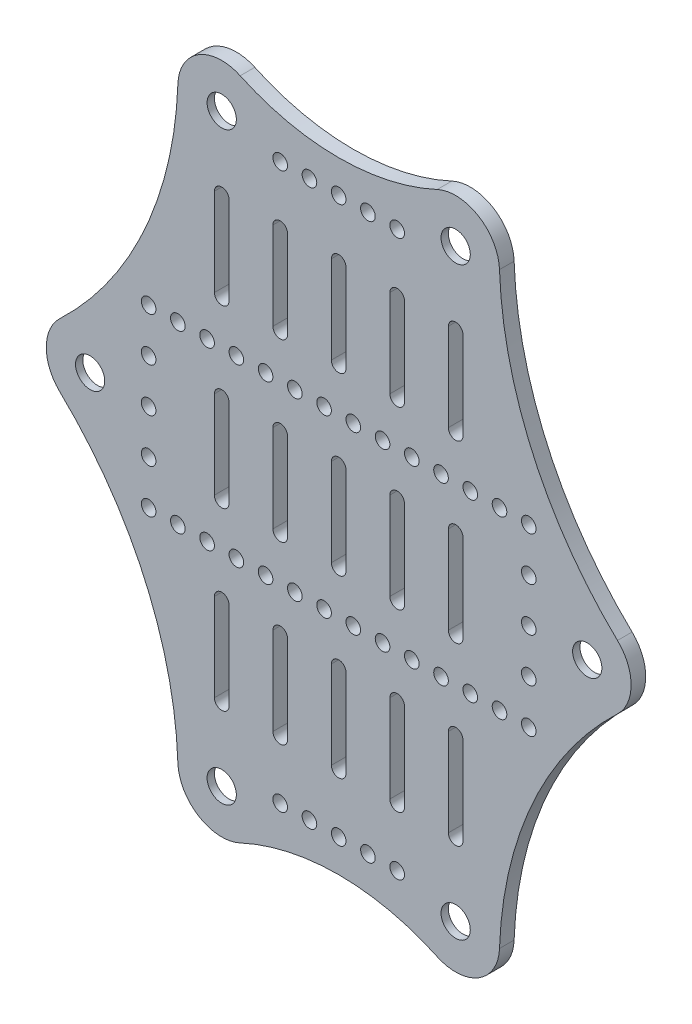
SolidWorks part; units mm, degrees
ref_plane "前视基准面" through (0, 0, 0) normal (0, 0, 1) x (1, 0, 0)
ref_plane "上视基准面" through (0, 0, 0) normal (0, 1, 0) x (1, 0, 0)
ref_plane "右视基准面" through (0, 0, 0) normal (1, 0, 0) x (0, 0, -1)
other "Configuration Table"
sketch "Sketch1" plane through (0, 0, 0) normal (0, 0, 1) x (1, 0, 0)
  line L0 (0, 0) -> (0, 100) construction
  line L1 (0, 100) -> (40, 100) construction
  line L2 (0, 0) -> (85, 0) construction
  circle A1 centre (85, 0) radius 15
  circle A2 centre (40, 100) radius 15
  circle A3 centre (-85, 0) radius 15
  circle A4 centre (-40, 100) radius 15
  circle A5 centre (40, -100) radius 15
  circle A6 centre (-40, -100) radius 15
  arc A7 (-33.6842, 113.6055) -> (33.6842, 113.6055) centre (0, 186.1684) ccw
  arc A8 (-33.6842, -113.6055) -> (33.6842, -113.6055) centre (0, -186.1684) cw
  arc A9 (-95.3356, 10.8708) -> (-54.9908, 100.526) centre (-184.9108, 105.0849) ccw
  arc A10 (95.3356, 10.8708) -> (54.9908, 100.526) centre (184.9108, 105.0849) cw
  arc A11 (95.3356, -10.8708) -> (54.9908, -100.526) centre (184.9108, -105.0849) ccw
  arc A12 (-95.3356, -10.8708) -> (-54.9908, -100.526) centre (-184.9108, -105.0849) cw
  dimension "D1" = 30
  dimension "D2" = 30
  dimension "D6" = 80
  dimension "D7" = 130
  dimension "D3" = 40
  dimension "D4" = 85
  dimension "D5" = 100
extrude "Boss-Extrude1" add sketch "Sketch1" along normal blind 5 contours A3 A12 A6 A8 A5 A11 A1 A10 A2 A7 A4 A9 | A3 | A4 | A2 | A1 | A5 | A6 A7
sketch "Sketch2" plane through (0, 0, 0) normal (0, 0, -1) x (-1, 0, 0)
  line L0 (0, 0) -> (0, 91.5521) construction
  line L1 (0, 0) -> (39.9574, 0) construction
  circle A0 centre (-40, 100) radius 5
  circle A1 centre (-85, 0) radius 5
  circle A2 centre (85, 0) radius 5
  circle A3 centre (40, 100) radius 5
  circle A4 centre (40, -100) radius 5
  circle A5 centre (-40, -100) radius 5
  dimension "D1" = 10
extrude "Cut-Extrude1" cut sketch "Sketch2" against normal through all
sketch "Sketch5" plane through (0, 0, 0) normal (0, 0, -1) x (-1, 0, 0)
  line L0 (0, 95) -> (0, 106.1684) construction
  line L1 (0, 95) -> (20, 95) construction
  line L2 (0, -95) -> (0, -106.1684) construction
  line L3 (0, 0) -> (50.0339, 0) construction
  line L5 (0, -95) -> (20, -95) construction
  circle A0 centre (20, 95) radius 2.5
  circle A1 centre (0, 95) radius 2.5
  circle A2 centre (10, 95) radius 2.5
  circle A17 centre (10, -95) radius 2.5
  circle A18 centre (0, -95) radius 2.5
  circle A19 centre (20, -95) radius 2.5
  arc A20 (-33.6842, 113.6055) -> (33.6842, 113.6055) centre (0, 186.1684) ccw construction
  circle A21 centre (-20, 95) radius 2.5
  circle A22 centre (-10, 95) radius 2.5
  arc A23 (33.6842, -113.6055) -> (-33.6842, -113.6055) centre (0, -186.1684) ccw construction
  circle A24 centre (-20, -95) radius 2.5
  circle A25 centre (-10, -95) radius 2.5
  dimension "D1" = 5
  dimension "D2" = 5
  dimension "D4" = 5
  dimension "D3" = 95
  dimension "D5" = 10
extrude "Cut-Extrude4" cut sketch "Sketch5" against normal blind 12.5
sketch "Sketch6" plane through (0, 0, 5) normal (0, 0, 1) x (1, 0, 0)
  line L110 (0, 0) -> (0, 75) construction
  line L111 (0, 75) -> (40, 75) construction
  line L112 (40, 75) -> (40, 45) construction
  line L113 (42.5, 75) -> (42.5, 45)
  line L114 (37.5, 75) -> (37.5, 45)
  line L115 (20, 75) -> (20, 45) construction
  line L116 (22.5, 75) -> (22.5, 45)
  line L117 (17.5, 75) -> (17.5, 45)
  line L118 (0, 75) -> (0, 45) construction
  line L119 (2.5, 75) -> (2.5, 45)
  line L120 (-2.5, 75) -> (-2.5, 45)
  line L121 (-20, 75) -> (-20, 45) construction
  line L122 (-17.5, 75) -> (-17.5, 45)
  line L123 (-22.5, 75) -> (-22.5, 45)
  line L124 (-40, 75) -> (-40, 45) construction
  line L125 (-37.5, 75) -> (-37.5, 45)
  line L126 (-42.5, 75) -> (-42.5, 45)
  line L127 (40, 100) -> (0, 100) construction
  line L128 (0, 15) -> (40, 15) construction
  line L129 (40, 15) -> (40, -15) construction
  line L130 (42.5, 15) -> (42.5, -15)
  line L131 (37.5, 15) -> (37.5, -15)
  line L132 (20, 15) -> (20, -15) construction
  line L133 (22.5, 15) -> (22.5, -15)
  line L134 (17.5, 15) -> (17.5, -15)
  line L135 (0, 15) -> (0, -15) construction
  line L136 (2.5, 15) -> (2.5, -15)
  line L137 (-2.5, 15) -> (-2.5, -15)
  line L138 (-20, 15) -> (-20, -15) construction
  line L139 (-17.5, 15) -> (-17.5, -15)
  line L140 (-22.5, 15) -> (-22.5, -15)
  line L141 (-40, 15) -> (-40, -15) construction
  line L142 (-37.5, 15) -> (-37.5, -15)
  line L143 (-42.5, 15) -> (-42.5, -15)
  line L144 (0, -45) -> (40, -45) construction
  line L145 (40, -45) -> (40, -75) construction
  line L146 (42.5, -45) -> (42.5, -75)
  line L147 (37.5, -45) -> (37.5, -75)
  line L148 (20, -45) -> (20, -75) construction
  line L149 (22.5, -45) -> (22.5, -75)
  line L150 (17.5, -45) -> (17.5, -75)
  line L151 (0, -45) -> (0, -75) construction
  line L152 (2.5, -45) -> (2.5, -75)
  line L153 (-2.5, -45) -> (-2.5, -75)
  line L154 (-20, -45) -> (-20, -75) construction
  line L155 (-17.5, -45) -> (-17.5, -75)
  line L156 (-22.5, -45) -> (-22.5, -75)
  line L157 (-40, -45) -> (-40, -75) construction
  line L158 (-37.5, -45) -> (-37.5, -75)
  line L159 (-42.5, -45) -> (-42.5, -75)
  arc A90 (42.5, 75) -> (37.5, 75) centre (40, 75) ccw
  arc A91 (37.5, 45) -> (42.5, 45) centre (40, 45) ccw
  arc A92 (22.5, 75) -> (17.5, 75) centre (20, 75) ccw
  arc A93 (17.5, 45) -> (22.5, 45) centre (20, 45) ccw
  arc A94 (2.5, 75) -> (-2.5, 75) centre (0, 75) ccw
  arc A95 (-2.5, 45) -> (2.5, 45) centre (0, 45) ccw
  arc A96 (-17.5, 75) -> (-22.5, 75) centre (-20, 75) ccw
  arc A97 (-22.5, 45) -> (-17.5, 45) centre (-20, 45) ccw
  arc A98 (-37.5, 75) -> (-42.5, 75) centre (-40, 75) ccw
  arc A99 (-42.5, 45) -> (-37.5, 45) centre (-40, 45) ccw
  arc A100 (42.5, 15) -> (37.5, 15) centre (40, 15) ccw
  arc A101 (37.5, -15) -> (42.5, -15) centre (40, -15) ccw
  arc A102 (22.5, 15) -> (17.5, 15) centre (20, 15) ccw
  arc A103 (17.5, -15) -> (22.5, -15) centre (20, -15) ccw
  arc A104 (2.5, 15) -> (-2.5, 15) centre (0, 15) ccw
  arc A105 (-2.5, -15) -> (2.5, -15) centre (0, -15) ccw
  arc A106 (-17.5, 15) -> (-22.5, 15) centre (-20, 15) ccw
  arc A107 (-22.5, -15) -> (-17.5, -15) centre (-20, -15) ccw
  arc A108 (-37.5, 15) -> (-42.5, 15) centre (-40, 15) ccw
  arc A109 (-42.5, -15) -> (-37.5, -15) centre (-40, -15) ccw
  arc A110 (42.5, -45) -> (37.5, -45) centre (40, -45) ccw
  arc A111 (37.5, -75) -> (42.5, -75) centre (40, -75) ccw
  arc A112 (22.5, -45) -> (17.5, -45) centre (20, -45) ccw
  arc A113 (17.5, -75) -> (22.5, -75) centre (20, -75) ccw
  arc A114 (2.5, -45) -> (-2.5, -45) centre (0, -45) ccw
  arc A115 (-2.5, -75) -> (2.5, -75) centre (0, -75) ccw
  arc A116 (-17.5, -45) -> (-22.5, -45) centre (-20, -45) ccw
  arc A117 (-22.5, -75) -> (-17.5, -75) centre (-20, -75) ccw
  arc A118 (-37.5, -45) -> (-42.5, -45) centre (-40, -45) ccw
  arc A119 (-42.5, -75) -> (-37.5, -75) centre (-40, -75) ccw
  point P111 (40, 100)
  point P115 (40, 60)
  point P123 (20, 60)
  point P130 (0, 60)
  point P137 (-20, 60)
  point P144 (-40, 60)
  point P153 (40, 0)
  point P160 (20, 0)
  point P167 (0, 0)
  point P174 (-20, 0)
  point P181 (-40, 0)
  point P189 (40, -60)
  point P196 (20, -60)
  point P203 (0, -60)
  point P210 (-20, -60)
  point P217 (-40, -60)
  dimension "D9" = 2.5
  dimension "D7" = 40
  dimension "D8" = 75
  dimension "D10" = 30
  dimension "D11" = 20
  dimension "D12" = 60
  dimension "D13" = 20
extrude "Cut-Extrude5" cut sketch "Sketch6" against normal blind 10
sketch "Sketch7" plane through (0, 0, 5) normal (0, 0, 1) x (1, 0, 0)
  line L4 (0, 0) -> (0, 30) construction
  line L5 (0, 30) -> (-65, 30) construction
  line L6 (0, 0) -> (85, 0) construction
  line L7 (0, -30) -> (-65, -30) construction
  circle A28 centre (-65, 30) radius 2.5
  circle A29 centre (-55, 30) radius 2.5
  circle A30 centre (-45, 30) radius 2.5
  circle A31 centre (-35, 30) radius 2.5
  circle A32 centre (-25, 30) radius 2.5
  circle A33 centre (-15, 30) radius 2.5
  circle A34 centre (-5, 30) radius 2.5
  circle A35 centre (5, 30) radius 2.5
  circle A36 centre (15, 30) radius 2.5
  circle A37 centre (25, 30) radius 2.5
  circle A38 centre (35, 30) radius 2.5
  circle A39 centre (45, 30) radius 2.5
  circle A40 centre (55, 30) radius 2.5
  circle A41 centre (65, 30) radius 2.5
  circle A42 centre (65, -30) radius 2.5
  circle A43 centre (55, -30) radius 2.5
  circle A44 centre (45, -30) radius 2.5
  circle A45 centre (35, -30) radius 2.5
  circle A46 centre (25, -30) radius 2.5
  circle A47 centre (15, -30) radius 2.5
  circle A48 centre (5, -30) radius 2.5
  circle A49 centre (-5, -30) radius 2.5
  circle A50 centre (-15, -30) radius 2.5
  circle A51 centre (-25, -30) radius 2.5
  circle A52 centre (-35, -30) radius 2.5
  circle A53 centre (-45, -30) radius 2.5
  circle A54 centre (-55, -30) radius 2.5
  circle A55 centre (-65, -30) radius 2.5
  dimension "D5" = 5
  dimension "D6" = 30
  dimension "D7" = 65
  dimension "D8" = 10
extrude "Cut-Extrude6" cut sketch "Sketch7" against normal blind 10
sketch "Sketch8" plane through (0, 0, 5) normal (0, 0, 1) x (1, 0, 0)
  line L5 (0, 0) -> (-65, 0) construction
  line L6 (-65, 0) -> (-40, 15) construction
  line L7 (-40, 15) -> (-65, 15) construction
  line L8 (-65, 15) -> (-65, 0) construction
  line L9 (0, 0) -> (0, 17.5) construction
  circle A6 centre (-65, 0) radius 2.5
  circle A7 centre (-65, 15) radius 2.5
  circle A8 centre (-65, -15) radius 2.5
  circle A9 centre (65, -15) radius 2.5
  circle A10 centre (65, 0) radius 2.5
  circle A11 centre (65, 15) radius 2.5
  dimension "D4" = 5
  dimension "D6" = 5
  dimension "D5" = 65
extrude "Cut-Extrude7" cut sketch "Sketch8" against normal blind 10
sketch "Sketch9" plane through (0, 0, 0) normal (0, 0, -1) x (-1, 0, 0)
  circle A1 centre (85, 0) radius 8.75
  circle A2 centre (40, 100) radius 8.75
  circle A3 centre (40, -100) radius 8.75
  circle A4 centre (-40, -100) radius 8.75
  circle A5 centre (-85, 0) radius 8.75
  circle A6 centre (-40, 100) radius 8.75
  dimension "D1" = 17.5
extrude "Cut-Extrude8" cut sketch "Sketch9" against normal blind 2.5
